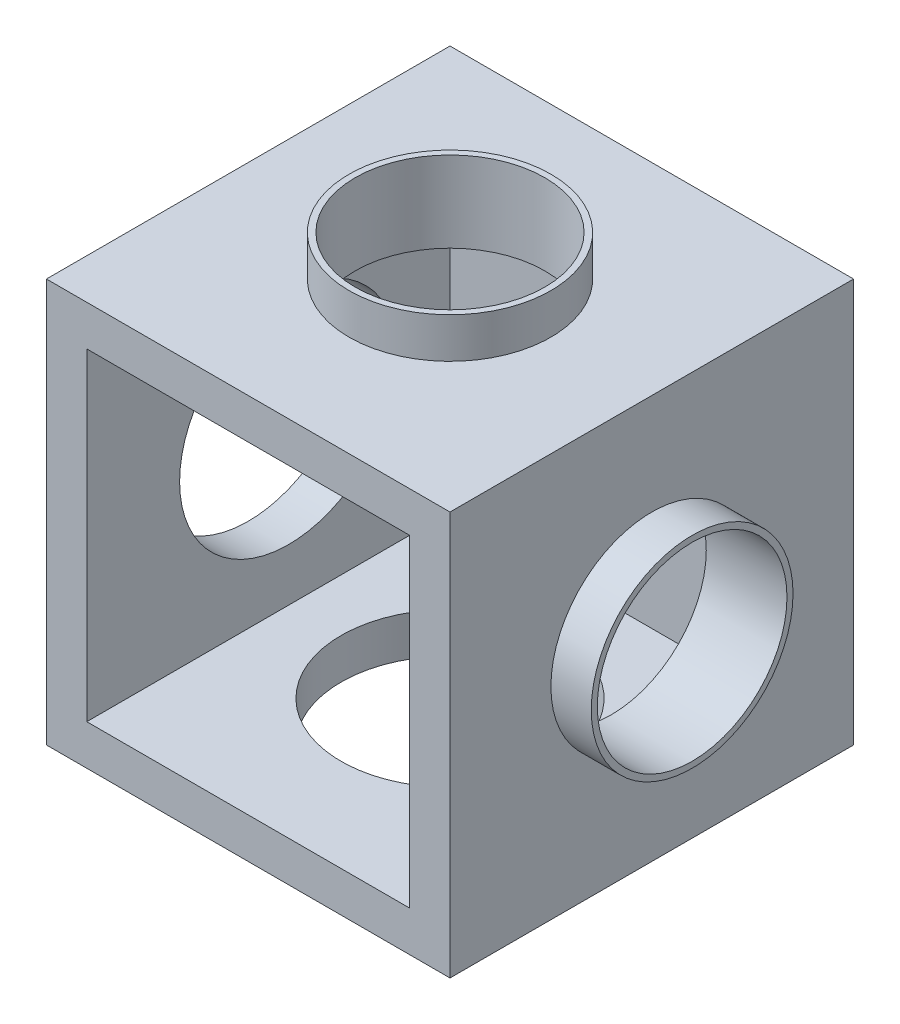
SolidWorks part; units mm, degrees
ref_plane "Front Plane" through (0, 0, 0) normal (0, 0, 1) x (1, 0, 0)
ref_plane "Top Plane" through (0, 0, 0) normal (0, 1, 0) x (1, 0, 0)
ref_plane "Right Plane" through (0, 0, 0) normal (1, 0, 0) x (0, 0, -1)
sketch "Sketch1" plane through (0, 0, 0) normal (0, 1, 0) x (1, 0, 0)
  line L1 (0, 0) -> (50, 0)
  line L2 (0, 0) -> (0, 50)
  line L3 (0, 50) -> (50, 50)
  line L4 (50, 0) -> (50, 50)
extrude "Boss-Extrude1" add sketch "Sketch1" along normal blind 50
sketch "Sketch2" plane through (0, 0, 0) normal (0, 0, 1) x (1, 0, 0)
  line L1 (5, 45) -> (45, 45)
  line L2 (5, 45) -> (5, 5)
  line L3 (5, 5) -> (45, 5)
  line L4 (45, 45) -> (45, 5)
extrude "Cut-Extrude1" cut sketch "Sketch2" against normal blind 45
sketch "Sketch3" plane through (0, 50, 0) normal (0, 1, 0) x (1, 0, 0)
  circle A0 centre (25, 25) radius 12.5
extrude "Boss-Extrude2" add sketch "Sketch3" along normal blind 5
sketch "Sketch4" plane through (0, 0, 0) normal (0, -1, 0) x (1, 0, 0)
  circle A0 centre (25, -25) radius 13.5
extrude "Cut-Extrude2" cut sketch "Sketch4" against normal blind 5
sketch "Sketch5" plane through (50, 0, 0) normal (1, 0, 0) x (0, 0, -1)
  circle A0 centre (25, 25) radius 12.5
extrude "Boss-Extrude3" add sketch "Sketch5" along normal blind 5
sketch "Sketch6" plane through (0, 0, 0) normal (-1, 0, 0) x (0, 0, 1)
  circle A0 centre (-25, 25) radius 13.5
extrude "Cut-Extrude3" cut sketch "Sketch6" against normal blind 5
sketch "Sketch7" plane through (0, 55, 0) normal (0, 1, 0) x (1, 0, 0)
  circle A0 centre (25, 25) radius 11.75
extrude "Cut-Extrude4" cut sketch "Sketch7" against normal blind 10
sketch "Sketch8" plane through (55, 0, 0) normal (1, 0, 0) x (0, 0, -1)
  circle A0 centre (25, 25) radius 11.75
extrude "Cut-Extrude5" cut sketch "Sketch8" against normal blind 10
